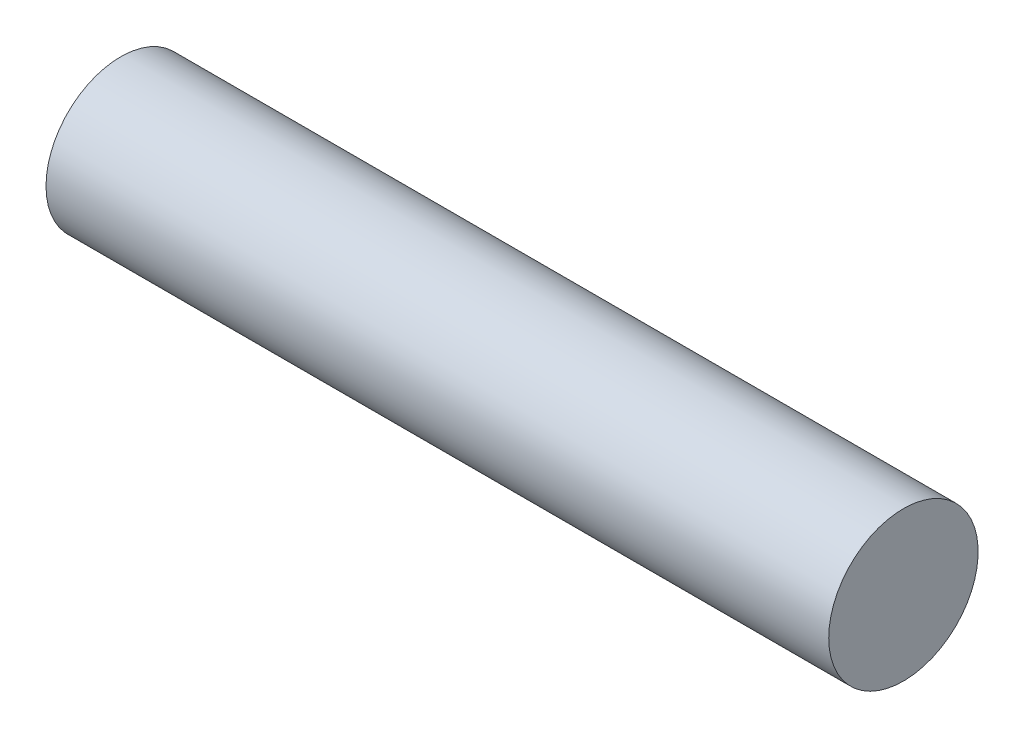
SolidWorks part; units mm, degrees
ref_plane "Front Plane" through (0, 0, 0) normal (0, 0, 1) x (1, 0, 0)
ref_plane "Top Plane" through (0, 0, 0) normal (0, 1, 0) x (1, 0, 0)
ref_plane "Right Plane" through (0, 0, 0) normal (1, 0, 0) x (0, 0, -1)
sketch "Sketch1" plane through (0, 0, 0) normal (0, 0, 1) x (1, 0, 0)
  line L0 (-150.2274, 0) -> (-139.2274, 0)
  line L1 (-139.2274, 0) -> (-139.2274, 1.05)
  line L2 (-139.2274, 1.05) -> (-150.2274, 1.05)
  line L3 (-150.2274, 1.05) -> (-150.2274, 0)
  dimension "D1" = 11
  dimension "D2" = 1.05
revolve "Revolve1" add sketch "Sketch1" angle 360 about L0
